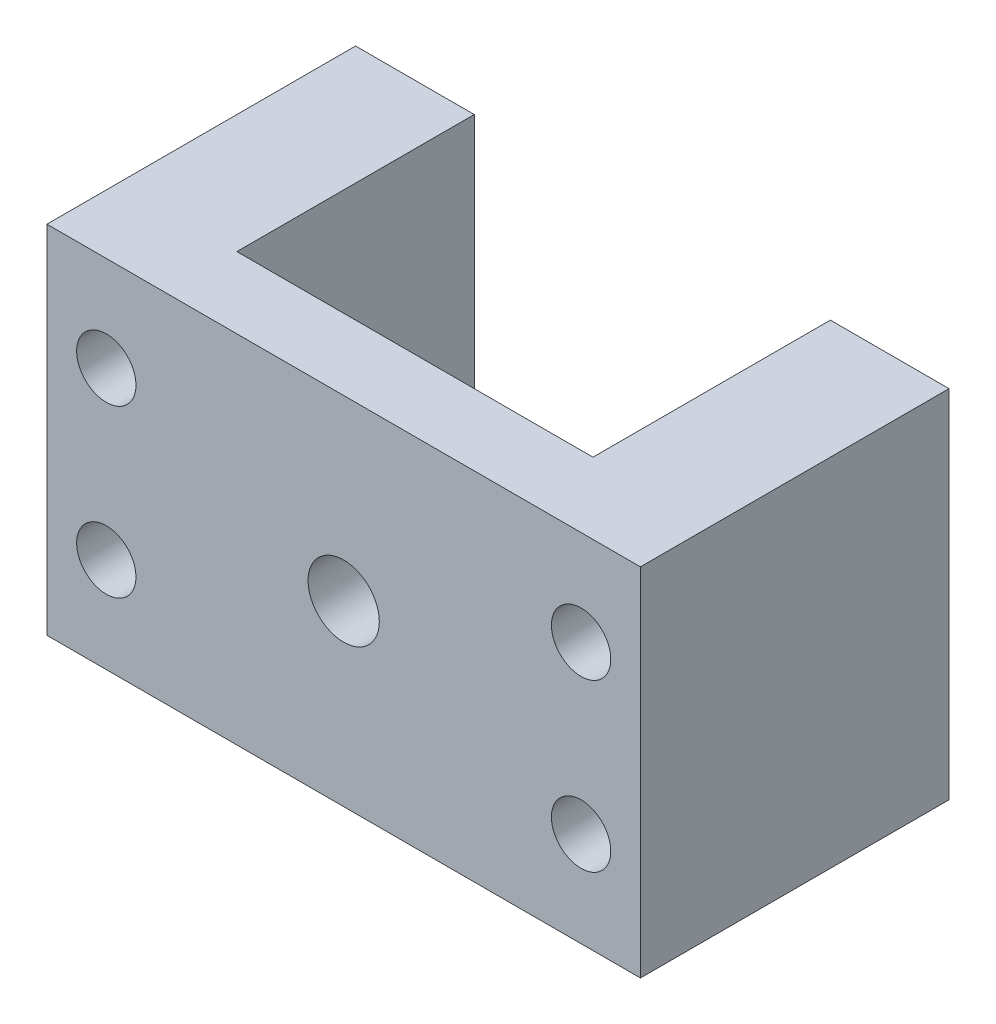
SolidWorks part; units mm, degrees
material "6061 合金"
ref_plane "前视基准面" through (0, 0, 0) normal (0, 0, 1) x (1, 0, 0)
ref_plane "上视基准面" through (0, 0, 0) normal (0, 1, 0) x (1, 0, 0)
ref_plane "右视基准面" through (0, 0, 0) normal (1, 0, 0) x (0, 0, -1)
sketch "草图1" plane through (0, 0, 0) normal (0, 1, 0) x (1, 0, 0)
  line L0 (0, 0) -> (-5, 0)
  line L2 (0, 0) -> (0, -11)
  line L3 (0, -11) -> (15, -11)
  line L4 (15, 0) -> (15, -11)
  line L6 (-5, 0) -> (-5, -15)
  line L7 (-5, -15) -> (20, -15)
  line L8 (20, 0) -> (20, -15)
  line L9 (15, 0) -> (20, 0)
  dimension "D1" = 5
  dimension "D2" = 11
  dimension "D3" = 15
  dimension "D4" = 5
  dimension "D5" = 4
extrude "凸台-拉伸1" add sketch "草图1" along normal blind 15
sketch "草图2" plane through (0, 0, 0) normal (0, 0, -1) x (-1, 0, 0)
  line L0 (-20, 0) -> (-15, 0) construction
  line L1 (-20, 15) -> (-15, 15) construction
  line L2 (-20, 15) -> (-20, 0) construction
  circle A0 centre (-17.5, 4) radius 1.25
  circle A1 centre (-17.5, 11) radius 1.25
  dimension "D1" = 2.5
  dimension "D2" = 2.5
  dimension "D3" = 4
  dimension "D4" = 4
  dimension "D5" = 2.5
  dimension "D6" = 2.5
extrude "切除-拉伸1" cut sketch "草图2" against normal through all
sketch "草图3" plane through (0, 0, 0) normal (0, 0, -1) x (-1, 0, 0)
  line L0 (0, 0) -> (5, 0) construction
  line L1 (0, 15) -> (5, 15) construction
  line L2 (5, 15) -> (5, 0) construction
  circle A0 centre (2.5, 4) radius 1.25
  circle A1 centre (2.5, 11) radius 1.25
  dimension "D1" = 4
  dimension "D2" = 4
  dimension "D3" = 2.5
  dimension "D4" = 2.5
  dimension "D5" = 2.5
  dimension "D6" = 2.5
extrude "切除-拉伸2" cut sketch "草图3" against normal through all
sketch "草图4" plane through (0, 0, 15) normal (0, 0, 1) x (1, 0, 0)
  line L0 (-5, 0) -> (20, 0) construction
  line L1 (20, 15) -> (20, 0) construction
  circle A0 centre (7.5, 7.5) radius 1.5
  dimension "D1" = 7.5
  dimension "D2" = 12.5
extrude "切除-拉伸3" cut sketch "草图4" against normal blind 18
sketch "草图5" plane through (0, 0, 0) normal (0, 0, -1) x (-1, 0, 0)
  line L1 (-20, 15) -> (5, 15)
  line L2 (-20, 15) -> (-20, 0)
  line L3 (-20, 0) -> (5, 0)
  line L4 (5, 15) -> (5, 0)
extrude "切除-拉伸4" cut sketch "草图5" against normal blind 1
sketch "草图6" plane through (0, 0, 15) normal (0, 0, 1) x (1, 0, 0)
  line L1 (-5, 15) -> (20, 15)
  line L2 (-5, 15) -> (-5, 0)
  line L3 (-5, 0) -> (20, 0)
  line L4 (20, 15) -> (20, 0)
extrude "切除-拉伸5" cut sketch "草图6" against normal blind 1
